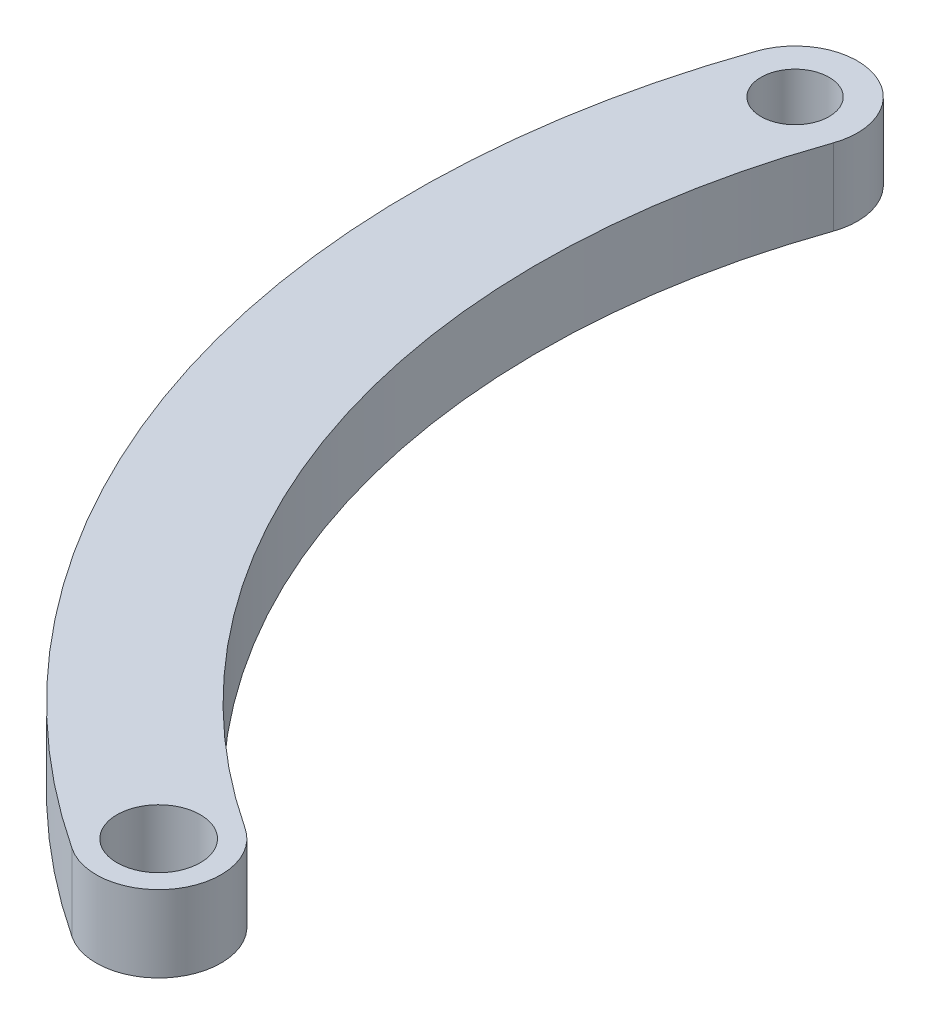
SolidWorks part; units mm, degrees
ref_plane "Front Plane" through (0, 0, 0) normal (0, 0, 1) x (1, 0, 0)
ref_plane "Top Plane" through (0, 0, 0) normal (0, 1, 0) x (1, 0, 0)
ref_plane "Right Plane" through (0, 0, 0) normal (1, 0, 0) x (0, 0, -1)
sketch "Sketch1" plane through (0, 0, 0) normal (0, 1, 0) x (1, 0, 0)
  arc A0 (-60.9481, 21.3773) -> (-35.5279, -53.9391) centre (0, 0) ccw construction
  arc A1 (-65.5657, 22.9969) -> (-38.2196, -58.0257) centre (0, 0) ccw
  arc A2 (-56.3304, 19.7577) -> (-32.8362, -49.8524) centre (0, 0) ccw
  arc A3 (-56.3304, 19.7577) -> (-65.5657, 22.9969) centre (-60.9481, 21.3773) ccw
  arc A4 (-38.2196, -58.0257) -> (-32.8362, -49.8524) centre (-35.5279, -53.9391) ccw
  circle A5 centre (-60.9481, 21.3773) radius 2.6719
  circle A6 centre (-35.5279, -53.9391) radius 3.2658
  point P4 (-61.1967, -20.6546)
extrude "Boss-Extrude1" add sketch "Sketch1" along normal blind 6
